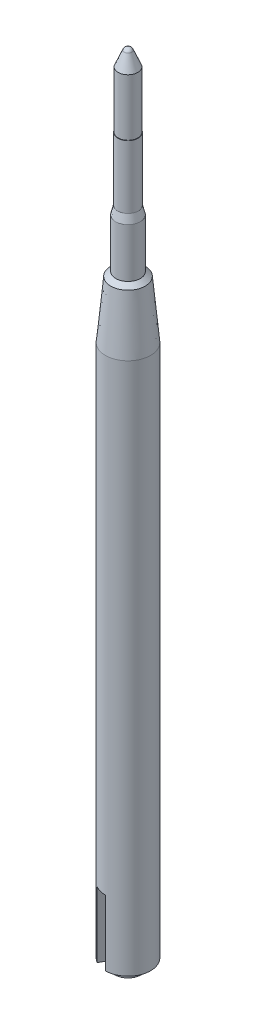
SolidWorks part; units mm, degrees
ref_plane "Ebene vorne" through (0, 0, 0) normal (0, 0, 1) x (1, 0, 0)
ref_plane "Ebene oben" through (0, 0, 0) normal (0, 1, 0) x (1, 0, 0)
ref_plane "Ebene rechts" through (0, 0, 0) normal (1, 0, 0) x (0, 0, -1)
sketch "Skizze1" plane through (0, 0, 0) normal (0, 0, 1) x (1, 0, 0)
  line L0 (0, 4.0104) -> (0, -135.6295) construction
  line L1 (0, 0) -> (1.25, -3) construction
  line L2 (1.25, -3) -> (1.25, -17.5) construction
  line L3 (1.25, -17.5) -> (1.5, -18.5)
  line L4 (1.5, -18.5) -> (1.5, -24.5)
  line L5 (1.5, -24.5) -> (2.1, -25)
  line L6 (2.1, -25) -> (2.75, -32)
  line L7 (2.75, -32) -> (2.75, -97)
  line L8 (2.75, -97) -> (1.6, -97)
  line L9 (1.6, -97) -> (1.6, -98)
  line L10 (1.6, -98) -> (0, -98)
  line L11 (0, -98) -> (0, 0) construction
  line L12 (0.4615, -1.1077) -> (1.25, -3) construction
  line L13 (0, -0.8) -> (0, -98)
  line L14 (8.6954, -9.8) -> (-4.9133, -9.8) construction
  line L15 (1.2, -9.8) -> (1.2, -2.88)
  line L16 (1.2, -9.8) -> (1.25, -9.8)
  line L17 (1.25, -9.8) -> (1.25, -17.5)
  line L18 (0.4615, -1.1077) -> (1.2, -2.88)
  arc A0 (0.4615, -1.1077) -> (0, -0.8) centre (0, -1.3) ccw
  dimension "D14" = 0.5
  dimension "D1" = 2.75
  dimension "D2" = 1.25
  dimension "D3" = 1.5
  dimension "D4" = 2.1
  dimension "D5" = 1.6
  dimension "D6" = 1
  dimension "D7" = 65
  dimension "D8" = 7
  dimension "D9" = 0.5
  dimension "D10" = 1
  dimension "D11" = 3
  dimension "D12" = 6
  dimension "D13" = 14.5
  dimension "D15" = 9
  dimension "D16" = 0.05
revolve "Rotation1" add sketch "Skizze1" angle 360 about L0
sketch "Skizze2" plane through (0, 0, 0) normal (1, 0, 0) x (0, 0, -1)
  line L0 (-1.6, -98) -> (1.6, -98) construction
  line L1 (-1.6, -89) -> (-4.6, -89)
  line L2 (-1.6, -89) -> (-1.6, -98)
  line L3 (-1.6, -98) -> (-4.6, -98)
  line L4 (-4.6, -89) -> (-4.6, -98)
  line L5 (-1.6, -89) -> (-4.6, -98) construction
  line L6 (-1.6, -98) -> (-4.6, -89) construction
  line L7 (1.6, -89) -> (4.6, -89)
  line L8 (1.6, -89) -> (1.6, -98)
  line L9 (1.6, -98) -> (4.6, -98)
  line L10 (4.6, -89) -> (4.6, -98)
  line L11 (1.6, -89) -> (4.6, -98) construction
  line L12 (1.6, -98) -> (4.6, -89) construction
  line L13 (0, -78.9679) -> (0, -103.4038) construction
  line L14 (1.6, -98) -> (1.6, -97) construction
  point P0 (-3.1, -93.5)
  point P5 (3.1, -93.5)
  dimension "D1" = 9
  dimension "D2" = 3
revolve "Schnitt-Rotation1" cut sketch "Skizze2" angle 30 about L13
